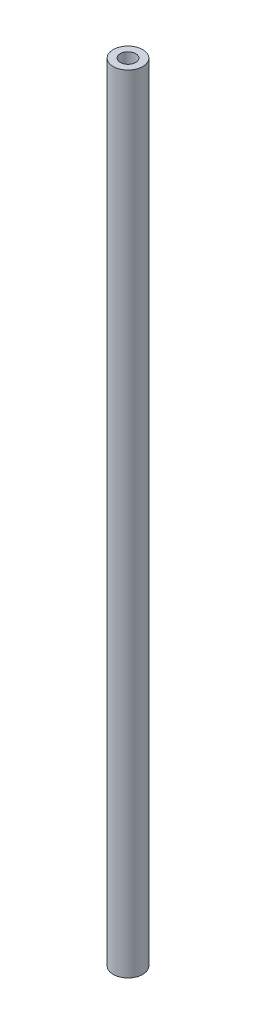
SolidWorks part; units mm, degrees
ref_plane "Front Plane" through (0, 0, 0) normal (0, 0, 1) x (1, 0, 0)
ref_plane "Top Plane" through (0, 0, 0) normal (0, 1, 0) x (1, 0, 0)
ref_plane "Right Plane" through (0, 0, 0) normal (1, 0, 0) x (0, 0, -1)
sketch "Sketch1" plane through (0, 0, 0) normal (0, 1, 0) x (1, 0, 0)
  circle A0 centre (0, 0) radius 4.7625
extrude "Boss-Extrude1" add sketch "Sketch1" along normal blind 254
sketch "Sketch2" plane through (0, 254, 0) normal (0, 1, 0) x (1, 0, 0)
  point P0 (0, 0)
hole_wizard "#10 Clearance Hole1" positions "Sketch4" profile "Sketch3" hole size "#10" standard "Ansi Inch"
sketch "Sketch4" plane through (0, 254, 0) normal (0, 1, 0) x (-1, 0, 0)
  point P1 (0, 0)
sketch "Sketch3" plane through (0, 254, 0) normal (1, 0, 0) x (0, 0, 1)
  line L0 (0, 0) -> (0, 2060.9257)
  line L1 (0, 2060.9257) -> (2.4892, 2059.43)
  line L2 (2.4892, 2059.43) -> (2.4892, 0)
  line L5 (2.4892, 0) -> (0, 0)
  line L10 (0, 2060.9257) -> (-2.4892, 2059.43) construction
  line L11 (0, -6.35) -> (0, 107.95) construction
  dimension "Hole Dia." = 4.9784
  dimension "Hole Depth" = 2059.43
  dimension "Drill Angle" = 118
